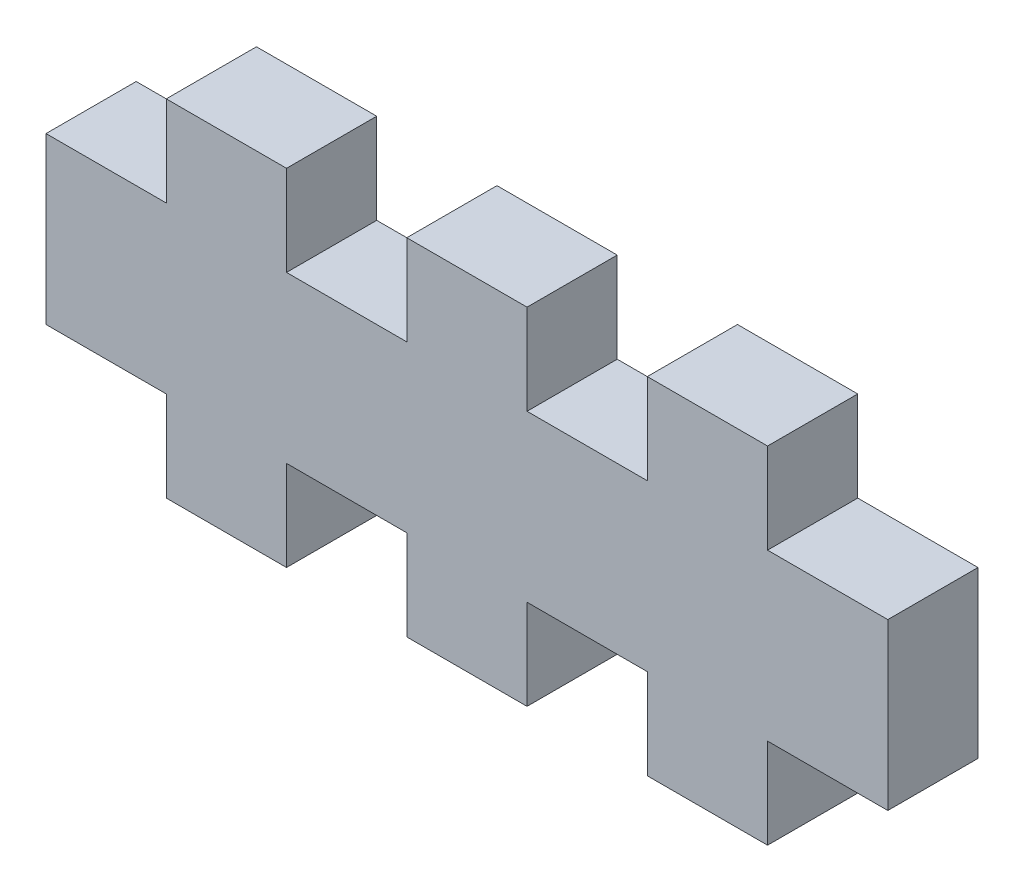
SolidWorks part; units mm, degrees
ref_plane "Alzado" through (0, 0, 0) normal (0, 0, 1) x (1, 0, 0)
ref_plane "Planta" through (0, 0, 0) normal (0, 1, 0) x (1, 0, 0)
ref_plane "Vista lateral" through (0, 0, 0) normal (1, 0, 0) x (0, 0, -1)
sketch "Croquis1" plane through (0, 0, 0) normal (0, 0, 1) x (1, 0, 0)
  line L0 (0, 0) -> (7.0658, 0) construction
  line L1 (-14, -5.75) -> (14, -5.75)
  line L2 (-14, -5.75) -> (-14, 5.75)
  line L3 (-14, 5.75) -> (14, 5.75)
  line L4 (14, -5.75) -> (14, 5.75)
  line L5 (-14, -5.75) -> (14, 5.75) construction
  line L6 (-14, 5.75) -> (14, -5.75) construction
  line L7 (-10, 5.75) -> (-6, 5.75)
  line L8 (-10, 5.75) -> (-10, 2.75)
  line L9 (-10, 2.75) -> (-6, 2.75)
  line L10 (-6, 5.75) -> (-6, 2.75)
  line L11 (-2, 5.75) -> (-2, 2.75)
  line L12 (-2, 5.75) -> (2, 5.75)
  line L13 (2, 5.75) -> (2, 2.75)
  line L14 (-2, 2.75) -> (2, 2.75)
  line L15 (6, 5.75) -> (6, 2.75)
  line L16 (6, 5.75) -> (10, 5.75)
  line L17 (10, 5.75) -> (10, 2.75)
  line L18 (6, 2.75) -> (10, 2.75)
  line L19 (6, -5.75) -> (10, -5.75)
  line L20 (10, -5.75) -> (10, -2.75)
  line L21 (6, -2.75) -> (10, -2.75)
  line L22 (6, -5.75) -> (6, -2.75)
  line L23 (-2, -5.75) -> (2, -5.75)
  line L24 (2, -5.75) -> (2, -2.75)
  line L25 (-2, -2.75) -> (2, -2.75)
  line L26 (-2, -5.75) -> (-2, -2.75)
  line L27 (-10, -2.75) -> (-6, -2.75)
  line L28 (-6, -5.75) -> (-6, -2.75)
  line L29 (-10, -5.75) -> (-6, -5.75)
  line L30 (-10, -5.75) -> (-10, -2.75)
  line L31 (-14, 2.75) -> (14, 2.75)
  line L32 (-14, -2.75) -> (14, -2.75)
  point P0 (0, 0)
  dimension "D1" = 28
  dimension "D2" = 11.5
  dimension "D3" = 4
  dimension "D4" = 3
  dimension "D5" = 4
  dimension "D7" = 4
  dimension "D6" = 3
extrude "Saliente-Extruir1" add sketch "Croquis1" along normal blind 3 contours L1 L30 L27 L28 L26 L25 L24 L22 L21 L20 L4 L3 L17 L18 L15 L13 L14 L11 L10 L9 L8 L2
